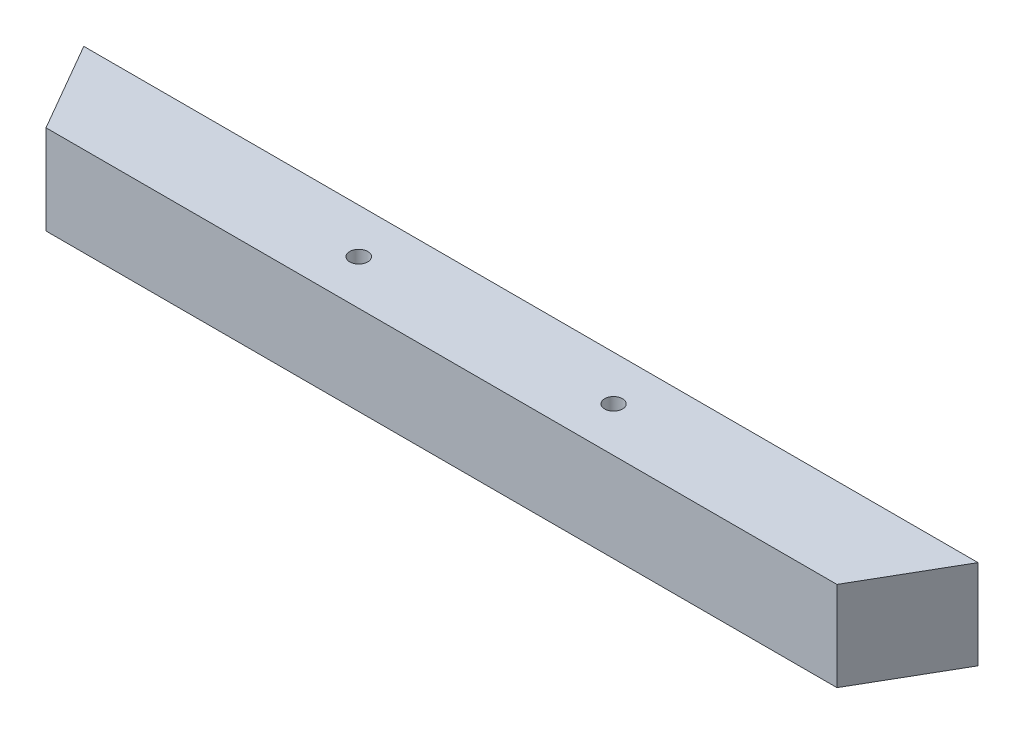
SolidWorks part; units mm, degrees
ref_plane "Front Plane" through (0, 0, 0) normal (0, 0, 1) x (1, 0, 0)
ref_plane "Top Plane" through (0, 0, 0) normal (0, 1, 0) x (1, 0, 0)
ref_plane "Right Plane" through (0, 0, 0) normal (1, 0, 0) x (0, 0, -1)
sketch "Sketch1" plane through (0, 0, 0) normal (0, 1, 0) x (1, 0, 0)
  line L0 (-100, 0) -> (100, 0)
  line L1 (-88.453, -20) -> (88.453, -20)
  line L2 (-100, 0) -> (-88.453, -20)
  line L3 (100, 0) -> (88.453, -20)
  circle A0 centre (-28.5, -10) radius 2.0196
  circle A1 centre (28.5, -10) radius 2
  point P4 (0, 0)
  point P7 (0, -20)
  point P13 (0, 0)
  point P14 (0, 0)
  dimension "D1" = 200
  dimension "D2" = 60
  dimension "D3" = 60
  dimension "D4" = 20
extrude "Boss-Extrude1" add sketch "Sketch1" along normal blind 20
